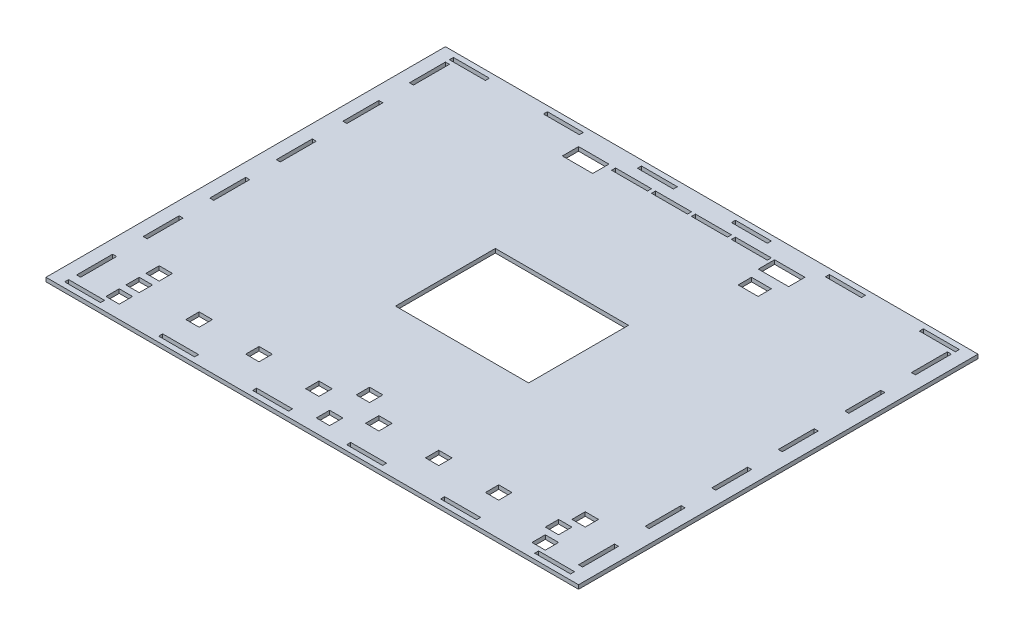
SolidWorks part; units mm, degrees
ref_plane "Plan de face" through (0, 0, 0) normal (0, 0, 1) x (1, 0, 0)
ref_plane "Plan de dessus" through (0, 0, 0) normal (0, 1, 0) x (1, 0, 0)
ref_plane "Plan de droite" through (0, 0, 0) normal (1, 0, 0) x (0, 0, -1)
sketch "Sketch1" plane through (0, 0, 0) normal (0, 1, 0) x (1, 0, 0)
  line L1 (-200, -150) -> (200, -150)
  line L2 (-200, -150) -> (-200, 150)
  line L3 (-200, 150) -> (200, 150)
  line L4 (200, -150) -> (200, 150)
  line L5 (-200, -150) -> (200, 150) construction
  line L6 (-200, 150) -> (200, -150) construction
  line L7 (50, -37.5) -> (-50, -37.5)
  line L8 (50, -37.5) -> (50, 37.5)
  line L9 (50, 37.5) -> (-50, 37.5)
  line L10 (-50, -37.5) -> (-50, 37.5)
  line L11 (50, -37.5) -> (-50, 37.5) construction
  line L12 (50, 37.5) -> (-50, -37.5) construction
  point P0 (0, 0)
  point P6 (0, 0)
  dimension "D1" = 400
  dimension "D2" = 300
  dimension "D3" = 100
  dimension "D4" = 75
extrude "Boss-Extrude2" add sketch "Sketch1" along normal blind 3
sketch "Sketch2" plane through (0, 3, 0) normal (0, 1, 0) x (1, 0, 0)
  line L0 (-200, -150) -> (200, -150) construction
  line L1 (-165, -125) -> (-155, -125)
  line L2 (-165, -125) -> (-165, -115)
  line L3 (-165, -115) -> (-155, -115)
  line L4 (-155, -125) -> (-155, -115)
  line L5 (-200, 150) -> (-200, -150) construction
  line L6 (-120, -125) -> (-120, -115)
  line L7 (-120, -125) -> (-110, -125)
  line L8 (-110, -125) -> (-110, -115)
  line L9 (-120, -115) -> (-110, -115)
  line L10 (-75, -125) -> (-75, -115)
  line L11 (-75, -125) -> (-65, -125)
  line L12 (-65, -125) -> (-65, -115)
  line L13 (-75, -115) -> (-65, -115)
  line L14 (-30, -125) -> (-30, -115)
  line L15 (-30, -125) -> (-20, -125)
  line L16 (-20, -125) -> (-20, -115)
  line L17 (-30, -115) -> (-20, -115)
  line L18 (15, -125) -> (15, -115)
  line L19 (15, -125) -> (25, -125)
  line L20 (25, -125) -> (25, -115)
  line L21 (15, -115) -> (25, -115)
  line L22 (60, -125) -> (60, -115)
  line L23 (60, -125) -> (70, -125)
  line L24 (70, -125) -> (70, -115)
  line L25 (60, -115) -> (70, -115)
  line L26 (105, -125) -> (105, -115)
  line L27 (105, -125) -> (115, -125)
  line L28 (115, -125) -> (115, -115)
  line L29 (105, -115) -> (115, -115)
  line L30 (150, -125) -> (150, -115)
  line L31 (150, -125) -> (160, -125)
  line L32 (160, -125) -> (160, -115)
  line L33 (150, -115) -> (160, -115)
  dimension "D1" = 10
  dimension "D2" = 10
  dimension "D3" = 25
  dimension "D4" = 35
  dimension "D5" = 8
extrude "Cut-Extrude1" cut sketch "Sketch2" against normal blind 3
sketch "Sketch3" plane through (0, 3, 0) normal (0, 1, 0) x (1, 0, 0)
  line L0 (200, 150) -> (-200, 150) construction
  line L1 (-85, 135) -> (-62.2, 135)
  line L2 (-85, 135) -> (-85, 122.8)
  line L3 (-85, 122.8) -> (-62.2, 122.8)
  line L4 (-62.2, 135) -> (-62.2, 122.8)
  line L5 (-200, 150) -> (-200, -150) construction
  line L6 (200, -150) -> (200, 150) construction
  line L7 (62.2, 122.8) -> (85, 122.8)
  line L8 (62.2, 122.8) -> (62.2, 135)
  line L9 (62.2, 135) -> (85, 135)
  line L10 (85, 122.8) -> (85, 135)
  dimension "D1" = 22.8
  dimension "D2" = 12.2
  dimension "D3" = 15
  dimension "D4" = 115
  dimension "D5" = 22.8
  dimension "D6" = 12.2
  dimension "D7" = 15
  dimension "D8" = 115
extrude "Cut-Extrude2" cut sketch "Sketch3" against normal blind 3
sketch "Sketch4" plane through (0, 3, 0) normal (0, 1, 0) x (1, 0, 0)
  line L1 (64.915, 114.9451) -> (79.915, 114.9451)
  line L2 (64.915, 114.9451) -> (64.915, 104.9451)
  line L3 (64.915, 104.9451) -> (79.915, 104.9451)
  line L4 (79.915, 114.9451) -> (79.915, 104.9451)
  dimension "D1" = 15
  dimension "D2" = 10
extrude "Cut-Extrude3" cut sketch "Sketch4" against normal blind 3
sketch "Sketch5" plane through (0, 3, 0) normal (0, 1, 0) x (1, 0, 0)
  line L0 (-200, 150) -> (-200, -150) construction
  line L1 (-190, 140) -> (-187, 140)
  line L2 (-190, 140) -> (-190, 113)
  line L3 (-190, 113) -> (-187, 113)
  line L4 (-187, 140) -> (-187, 113)
  line L5 (200, 150) -> (-200, 150) construction
  line L6 (-190, 90) -> (-190, 63)
  line L7 (-190, 90) -> (-187, 90)
  line L8 (-187, 90) -> (-187, 63)
  line L9 (-190, 63) -> (-187, 63)
  line L10 (-190, 40) -> (-190, 13)
  line L11 (-190, 40) -> (-187, 40)
  line L12 (-187, 40) -> (-187, 13)
  line L13 (-190, 13) -> (-187, 13)
  line L14 (-190, -10) -> (-190, -37)
  line L15 (-190, -10) -> (-187, -10)
  line L16 (-187, -10) -> (-187, -37)
  line L17 (-190, -37) -> (-187, -37)
  line L18 (-190, -60) -> (-190, -87)
  line L19 (-190, -60) -> (-187, -60)
  line L20 (-187, -60) -> (-187, -87)
  line L21 (-190, -87) -> (-187, -87)
  line L22 (-190, -110) -> (-190, -137)
  line L23 (-190, -110) -> (-187, -110)
  line L24 (-187, -110) -> (-187, -137)
  line L25 (-190, -137) -> (-187, -137)
  dimension "D1" = 3
  dimension "D2" = 27
  dimension "D3" = 10
  dimension "D4" = 10
  dimension "D5" = 6
extrude "Cut-Extrude4" cut sketch "Sketch5" against normal blind 3
sketch "Sketch6" plane through (0, 3, 0) normal (0, 1, 0) x (1, 0, 0)
  line L0 (200, -150) -> (200, 150) construction
  line L1 (187, 140) -> (190, 140)
  line L2 (187, 140) -> (187, 113)
  line L3 (187, 113) -> (190, 113)
  line L4 (190, 140) -> (190, 113)
  line L5 (200, 150) -> (-200, 150) construction
  line L6 (187, 90) -> (187, 63)
  line L7 (187, 90) -> (190, 90)
  line L8 (190, 90) -> (190, 63)
  line L9 (187, 63) -> (190, 63)
  line L10 (187, 40) -> (187, 13)
  line L11 (187, 40) -> (190, 40)
  line L12 (190, 40) -> (190, 13)
  line L13 (187, 13) -> (190, 13)
  line L14 (187, -10) -> (187, -37)
  line L15 (187, -10) -> (190, -10)
  line L16 (190, -10) -> (190, -37)
  line L17 (187, -37) -> (190, -37)
  line L18 (187, -60) -> (187, -87)
  line L19 (187, -60) -> (190, -60)
  line L20 (190, -60) -> (190, -87)
  line L21 (187, -87) -> (190, -87)
  line L22 (187, -110) -> (187, -137)
  line L23 (187, -110) -> (190, -110)
  line L24 (190, -110) -> (190, -137)
  line L25 (187, -137) -> (190, -137)
  dimension "D1" = 3
  dimension "D2" = 27
  dimension "D3" = 10
  dimension "D4" = 10
  dimension "D5" = 6
extrude "Cut-Extrude5" cut sketch "Sketch6" against normal blind 3
sketch "Sketch7" plane through (0, 3, 0) normal (0, 1, 0) x (1, 0, 0)
  line L0 (-62.2, 135) -> (-85, 135) construction
  line L1 (-57.2, 135) -> (-30.2, 135)
  line L2 (-57.2, 135) -> (-57.2, 132)
  line L3 (-57.2, 132) -> (-30.2, 132)
  line L4 (-30.2, 135) -> (-30.2, 132)
  line L6 (-62.2, 122.8) -> (-62.2, 135) construction
  line L7 (-27.2, 135) -> (-27.2, 132)
  line L8 (-27.2, 135) -> (-0.2, 135)
  line L9 (-0.2, 135) -> (-0.2, 132)
  line L10 (-27.2, 132) -> (-0.2, 132)
  line L11 (2.8, 135) -> (2.8, 132)
  line L12 (2.8, 135) -> (29.8, 135)
  line L13 (29.8, 135) -> (29.8, 132)
  line L14 (2.8, 132) -> (29.8, 132)
  line L15 (32.8, 135) -> (32.8, 132)
  line L16 (32.8, 135) -> (59.8, 135)
  line L17 (59.8, 135) -> (59.8, 132)
  line L18 (32.8, 132) -> (59.8, 132)
  dimension "D1" = 0
  dimension "D2" = 3
  dimension "D3" = 27
  dimension "D4" = 5
  dimension "D5" = 4
extrude "Cut-Extrude6" cut sketch "Sketch7" against normal blind 3
sketch "Sketch8" plane through (0, 3, 0) normal (0, 1, 0) x (1, 0, 0)
  line L0 (-200, -150) -> (200, -150) construction
  line L1 (-165, -130) -> (-155, -130)
  line L2 (-165, -130) -> (-165, -140)
  line L3 (-165, -140) -> (-155, -140)
  line L4 (-155, -130) -> (-155, -140)
  line L5 (-200, 150) -> (-200, -150) construction
  line L6 (-165, -100) -> (-165, -110)
  line L7 (-165, -100) -> (-155, -100)
  line L8 (-155, -100) -> (-155, -110)
  line L9 (-165, -110) -> (-155, -110)
  dimension "D1" = 10
  dimension "D2" = 35
  dimension "D3" = 10
  dimension "D4" = 10
  dimension "D5" = 2
extrude "Cut-Extrude7" cut sketch "Sketch8" against normal blind 3
sketch "Sketch9" plane through (0, 3, 0) normal (0, 1, 0) x (1, 0, 0)
  line L0 (-200, -150) -> (200, -150) construction
  line L1 (-7, -130) -> (3, -130)
  line L2 (-7, -130) -> (-7, -140)
  line L3 (-7, -140) -> (3, -140)
  line L4 (3, -130) -> (3, -140)
  line L5 (-200, 150) -> (-200, -150) construction
  line L6 (-7, -100) -> (-7, -110)
  line L7 (-7, -100) -> (3, -100)
  line L8 (3, -100) -> (3, -110)
  line L9 (-7, -110) -> (3, -110)
  dimension "D1" = 10
  dimension "D2" = 10
  dimension "D3" = 10
  dimension "D4" = 193
  dimension "D5" = 2
extrude "Cut-Extrude8" cut sketch "Sketch9" against normal blind 3
sketch "Sketch11" plane through (0, 3, 0) normal (0, 1, 0) x (1, 0, 0)
  line L0 (-200, -150) -> (200, -150) construction
  line L1 (155, -130) -> (165, -130)
  line L2 (155, -130) -> (155, -140)
  line L3 (155, -140) -> (165, -140)
  line L4 (165, -130) -> (165, -140)
  line L5 (200, -150) -> (200, 150) construction
  line L6 (155, -100) -> (155, -110)
  line L7 (155, -100) -> (165, -100)
  line L8 (165, -100) -> (165, -110)
  line L9 (155, -110) -> (165, -110)
  dimension "D1" = 10
  dimension "D2" = 10
  dimension "D3" = 10
  dimension "D4" = 35
  dimension "D5" = 2
extrude "Cut-Extrude9" cut sketch "Sketch11" against normal blind 3
sketch "Sketch12" plane through (0, 0, 0) normal (0, -1, 0) x (1, 0, 0)
  line L0 (200, -150) -> (-200, -150) construction
  line L1 (-190, -143) -> (-163, -143)
  line L2 (-190, -143) -> (-190, -146)
  line L3 (-190, -146) -> (-163, -146)
  line L4 (-163, -143) -> (-163, -146)
  line L5 (-200, -150) -> (-200, 150) construction
  line L6 (-119.4, -143) -> (-119.4, -146)
  line L7 (-119.4, -143) -> (-92.4, -143)
  line L8 (-92.4, -143) -> (-92.4, -146)
  line L9 (-119.4, -146) -> (-92.4, -146)
  line L10 (-48.8, -143) -> (-48.8, -146)
  line L11 (-48.8, -143) -> (-21.8, -143)
  line L12 (-21.8, -143) -> (-21.8, -146)
  line L13 (-48.8, -146) -> (-21.8, -146)
  line L14 (21.8, -143) -> (21.8, -146)
  line L15 (21.8, -143) -> (48.8, -143)
  line L16 (48.8, -143) -> (48.8, -146)
  line L17 (21.8, -146) -> (48.8, -146)
  line L18 (92.4, -143) -> (92.4, -146)
  line L19 (92.4, -143) -> (119.4, -143)
  line L20 (119.4, -143) -> (119.4, -146)
  line L21 (92.4, -146) -> (119.4, -146)
  line L22 (163, -143) -> (163, -146)
  line L23 (163, -143) -> (190, -143)
  line L24 (190, -143) -> (190, -146)
  line L25 (163, -146) -> (190, -146)
  dimension "D1" = 27
  dimension "D2" = 3
  dimension "D3" = 4
  dimension "D4" = 10
  dimension "D5" = 4
  dimension "D6" = 6
extrude "Cut-Extrude10" cut sketch "Sketch12" against normal blind 10
sketch "Sketch13" plane through (0, 0, 0) normal (0, -1, 0) x (-1, 0, 0)
  line L1 (190, -146) -> (163, -146)
  line L2 (190, -146) -> (190, -143)
  line L3 (190, -143) -> (163, -143)
  line L4 (163, -146) -> (163, -143)
  line L5 (190, -110) -> (190, -137) construction
  line L6 (200, 150) -> (200, -150) construction
  line L7 (190, 143) -> (190, 146) construction
  line L8 (200, -150) -> (-200, -150) construction
  line L9 (119.4, -146) -> (119.4, -143)
  line L10 (119.4, -146) -> (92.4, -146)
  line L11 (92.4, -146) -> (92.4, -143)
  line L12 (119.4, -143) -> (92.4, -143)
  line L13 (48.8, -146) -> (48.8, -143)
  line L14 (48.8, -146) -> (21.8, -146)
  line L15 (21.8, -146) -> (21.8, -143)
  line L16 (48.8, -143) -> (21.8, -143)
  line L17 (-21.8, -146) -> (-21.8, -143)
  line L18 (-21.8, -146) -> (-48.8, -146)
  line L19 (-48.8, -146) -> (-48.8, -143)
  line L20 (-21.8, -143) -> (-48.8, -143)
  line L21 (-92.4, -146) -> (-92.4, -143)
  line L22 (-92.4, -146) -> (-119.4, -146)
  line L23 (-119.4, -146) -> (-119.4, -143)
  line L24 (-92.4, -143) -> (-119.4, -143)
  line L25 (-163, -146) -> (-163, -143)
  line L26 (-163, -146) -> (-190, -146)
  line L27 (-190, -146) -> (-190, -143)
  line L28 (-163, -143) -> (-190, -143)
  line L29 (190, -137) -> (187, -137) construction
  line L30 (-187, -137) -> (-190, -137) construction
  dimension "D1" = 27
  dimension "D2" = 3
  dimension "D3" = 0
  dimension "D4" = 10
  dimension "D5" = 10
  dimension "D6" = 4
  dimension "D8" = 9
  dimension "D9" = 9
  dimension "D7" = 6
extrude "Cut-Extrude11" cut sketch "Sketch13" against normal blind 10
